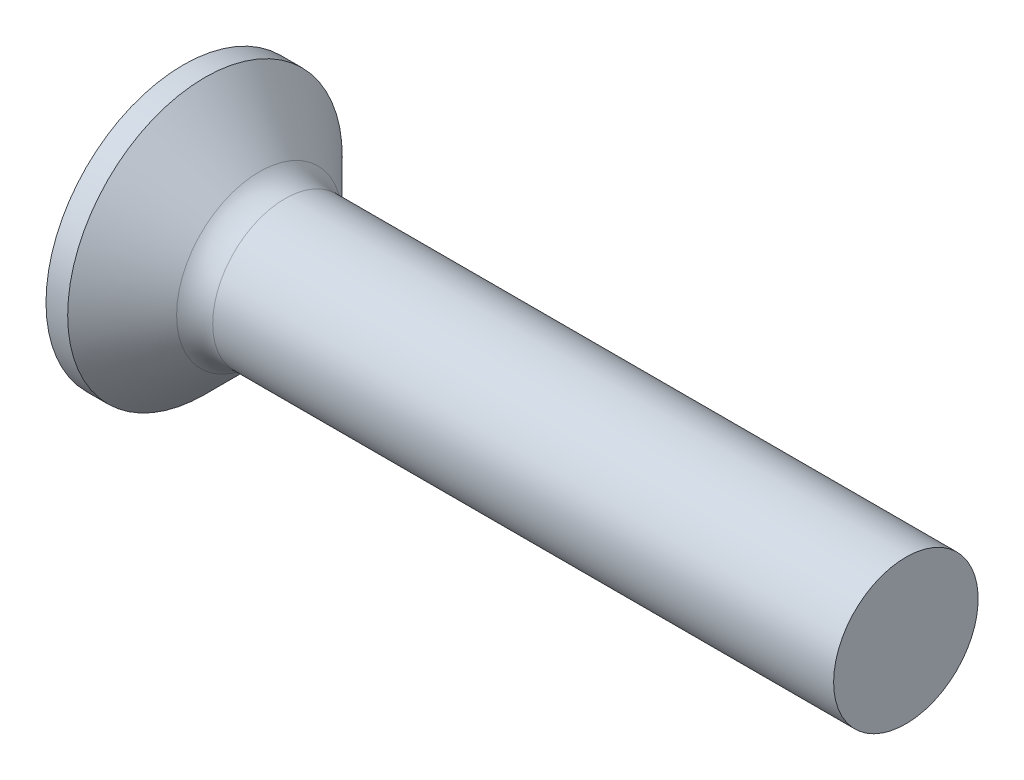
SolidWorks part; units mm, degrees
ref_plane "Plane1" through (0, 0, 0) normal (0, 0, 1) x (1, 0, 0)
ref_plane "Plane2" through (0, 0, 0) normal (0, 1, 0) x (1, 0, 0)
ref_plane "Plane3" through (0, 0, 0) normal (1, 0, 0) x (0, 0, -1)
sketch "BodySke" plane through (0, 0, 0) normal (0, 0, 1) x (1, 0, 0)
  line L0 (0, 0) -> (0, 1.9)
  line L1 (0, 1.9) -> (0.3, 1.9)
  line L2 (1.2, 1) -> (10, 1)
  line L3 (10, 1) -> (10, 0)
  line L4 (10, 0) -> (0, 0)
  line L5 (-6.35, 0) -> (82.55, 0) construction
  line L6 (1.2, -1) -> (10, -1) construction
  line L7 (0.3, -1.9) -> (1.2, -1) construction
  line L8 (0.3, 1.9) -> (1.2, 1)
  line L9 (0, -1.9) -> (0.3, -1.9) construction
  line L10 (1.6, 2.5875) -> (1.6, -6.9375) construction
  line L11 (2, 6.35) -> (2, -3.175) construction
  dimension "Diameter" = 2
  dimension "Length" = 10
  dimension "Head_ht" = 1.2
  dimension "Head_dia" = 3.8
  dimension "Head_ang" = 90
  dimension "D6" = 0.3
  dimension "Advance" = 0.4
  dimension "Thread_nom" = 8
revolve "Base-Revolve" add sketch "BodySke"
cosmetic thread "ThreadCosmetic" [suppressed]
fillet "Fillet1" radius 0.5 1 edges at (1.2, 0, 1)
sketch "Sketch3" plane through (0, 0, 0) normal (-1, 0, 0) x (0, 0, 1)
  line L0 (-0.24, 0.95) -> (0.24, 0.95)
  line L1 (0.24, 0.95) -> (0.24, -0.95)
  line L2 (0.24, -0.95) -> (-0.24, -0.95)
  line L3 (-0.24, -0.95) -> (-0.24, 0.95)
  dimension "D1" = 0.95
  dimension "Cross_dia" = 1.9
  dimension "D2" = 0.24
  dimension "Cross_width" = 0.48
ref_plane "Plane4" through (1.2, 0, 0) normal (-1, 0, 0) x (0, 0, 1)
sketch "Sketch4" plane through (1.2, 0, 0) normal (-1, 0, 0) x (0, 0, 1)
  line L0 (-0.24, 0.3517) -> (0.24, 0.3517)
  line L3 (0.24, 0.3517) -> (0.24, -0.3517)
  line L4 (0.24, -0.3517) -> (-0.24, -0.3517)
  line L5 (-0.24, -0.3517) -> (-0.24, 0.3517)
  dimension "D1" = 0.48
  dimension "D2" = 0.7034
  dimension "D3" = 0.24
  dimension "D4" = 0.3517
loft "Recess" cut profiles "Sketch3", "Sketch4"
pattern_circular "RecPat" count 2 every 90 about axis through (0, 0, 0) along (1, 0, 0) of "Recess"
sketch "RecCorSke" plane through (0, 0, 0) normal (0, 0, 1) x (1, 0, 0)
  line L0 (-3.175, 0) -> (15.875, 0) construction
  line L2 (0, 0) -> (0, 0.4394)
  line L3 (0, 0.4394) -> (1.2, 0.3555)
  line L4 (1.2, 0.3555) -> (1.3155, 0)
  line L5 (1.3155, 0) -> (0, 0)
  dimension "Diameter" = 0.711
  dimension "Depth" = 1.2
  dimension "Draft_angle" = 4
  dimension "Bottom_angle" = 18
revolve "RecessCore" cut sketch "RecCorSke" angle 360 about L0
sketch "ThdSchSke" plane through (0, 0, 0) normal (0, 0, 1) x (1, 0, 0)
  line L0 (2, -0.774) -> (1.8418, -1)
  line L1 (2, -0.774) -> (2.1582, -1)
  line L2 (2.1582, -1) -> (2.1582, -1.25)
  line L3 (-3.175, 0) -> (5.1513, 0) construction
  line L5 (2.1582, -1.25) -> (1.8418, -1.25)
  line L6 (1.8418, -1.25) -> (1.8418, -1)
  line L7 (0, 1.9) -> (0, -1.9) construction
  dimension "Thread_minor" = 1.548
  dimension "Diameter" = 2
  dimension "Start" = 2
  dimension "SideAngle" = 55
  dimension "VeeAngle" = 70
  dimension "Overcut" = 2.5
revolve "ThreadSchematic" [suppressed] cut sketch "ThdSchSke" angle 360 about L3
pattern_linear "ThdSchPat" [suppressed]
equation "\"D1@Sketch3\" = \"Cross_dia@Sketch3\" / 2"
equation "\"D2@Sketch3\" = \"Cross_width@Sketch3\" / 2"
equation "\"Depth@RecCorSke\" = \"Cross_depth@Plane4\""
equation "\"D1@Sketch4\" = \"Cross_width@Sketch3\""
equation "\"D2@Sketch4\" = \"Cross_dia@Sketch3\" - 2.0 * \"Cross_depth@Plane4\" * tan(26.5  * 0.017453292)"
equation "\"D3@Sketch4\" = \"D1@Sketch4\" / 2"
equation "\"D4@Sketch4\" = \"D2@Sketch4\" / 2"
equation "\"Thread_length@ThreadCosmetic\" = ((sgn( (\"Length@BodySke\" - \"Advance@BodySke\" * 1.0 - \"Head_ht@BodySke\" ) - \"Thread_nom@BodySke\" )-1)*( (\"Length@BodySke\" - \"Advance@BodySke\" * 1.0 - \"Head_ht@BodySke\" ) - \"Thread_nom@BodySke\" ))/-2+ \"Thread_nom@BodySke\""
equation "\"Thread_minor@ThdSchSke\" = \"Thread_minor@ThreadCosmetic\""
equation "\"Diameter@ThdSchSke\" = \"Diameter@BodySke\""
equation "\"Overcut@ThdSchSke\" = \"Diameter@BodySke\" * 1.25"
equation "\"Start@ThdSchSke\" = 0.000001 + \"Length@BodySke\" - \"Thread_length@ThreadCosmetic\"  '---Countersunk---"
equation "\"Num_threads@ThdSchPat\" = int( \"Thread_length@ThreadCosmetic\" / \"Advance@BodySke\" + 0.999 )  + 1"
equation "\"Advance@ThdSchPat\" = \"Thread_length@ThreadCosmetic\" /  (\"Num_threads@ThdSchPat\" - 1) 'relax it"
